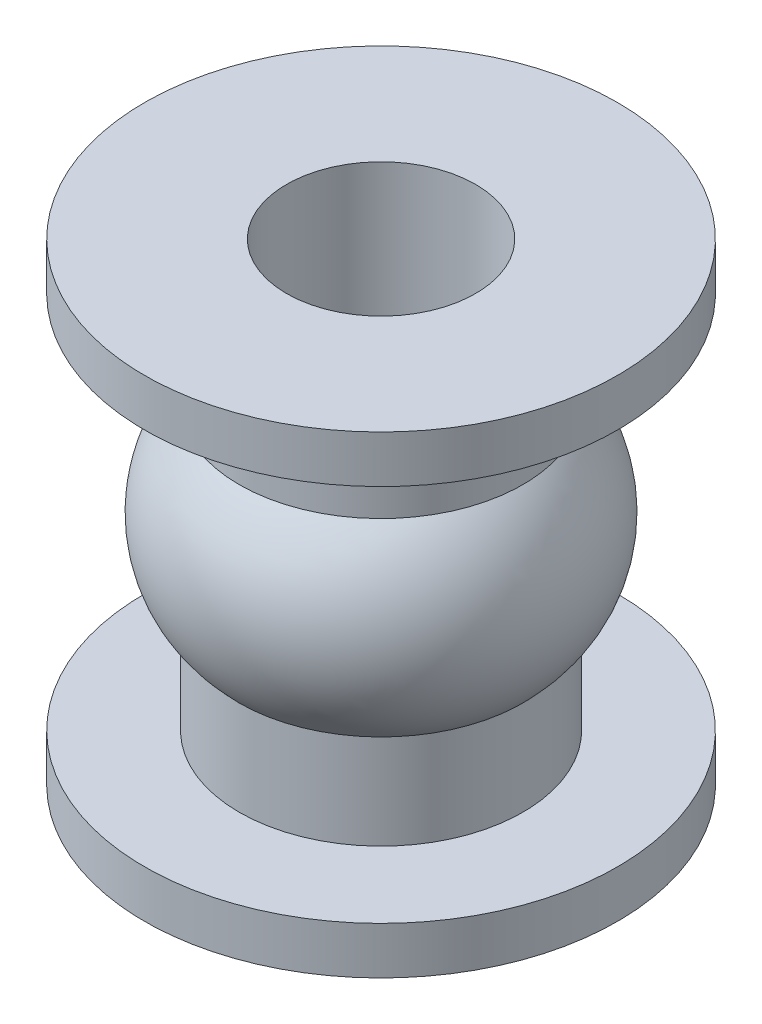
SolidWorks part; units mm, degrees
ref_plane "Alzado" through (0, 0, 0) normal (0, 0, 1) x (1, 0, 0)
ref_plane "Planta" through (0, 0, 0) normal (0, 1, 0) x (1, 0, 0)
ref_plane "Vista lateral" through (0, 0, 0) normal (1, 0, 0) x (0, 0, -1)
sketch "Croquis1" plane through (0, 0, 0) normal (0, 0, 1) x (1, 0, 0)
  line L0 (0, 0) -> (0, 10) construction
  line L1 (0, 10) -> (-2, 10) construction
  line L2 (-2, 10) -> (-2, 0) construction
  line L3 (-2, 0) -> (0, 0) construction
  line L4 (-2, 10) -> (-5, 10)
  line L5 (-5, 10) -> (-5, 9)
  line L6 (-5, 9) -> (-3, 9)
  line L8 (-3, 1) -> (-5, 1)
  line L9 (-5, 1) -> (-5, 0)
  line L10 (-5, 0) -> (-2, 0)
  line L11 (-2, 0) -> (-2, 10)
  line L12 (-3, 9) -> (-3, 7)
  line L13 (-3, 1) -> (-3, 3)
  arc A1 (-3, 7) -> (-3, 3) centre (-1, 5) ccw
  dimension "D1" = 10
  dimension "D2" = 2
  dimension "D3" = 1
  dimension "D4" = 3
  dimension "D5" = 2
  dimension "D6" = 1
  dimension "D7" = 2
  dimension "D8" = 2
revolve "Revolución1" add sketch "Croquis1" angle 360 about L0
